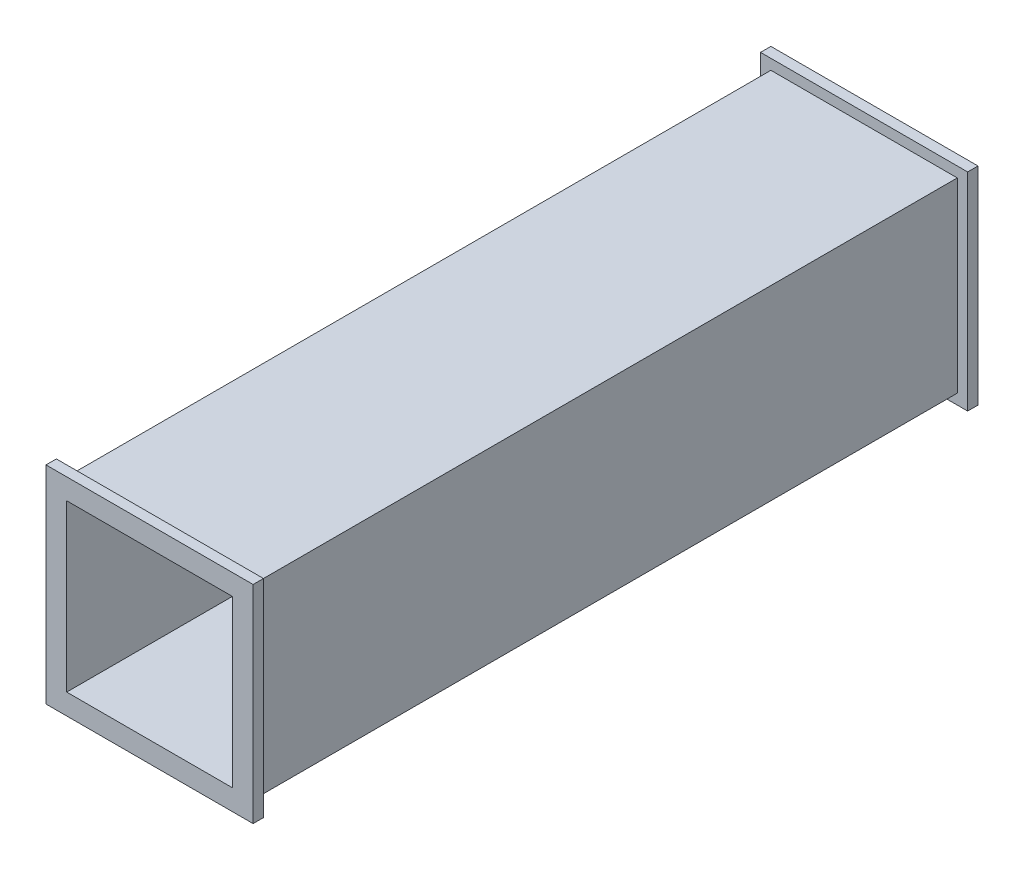
SolidWorks part; units mm, degrees
ref_plane "Front Plane" through (0, 0, 0) normal (0, 0, 1) x (1, 0, 0)
ref_plane "Top Plane" through (0, 0, 0) normal (0, 1, 0) x (1, 0, 0)
ref_plane "Right Plane" through (0, 0, 0) normal (1, 0, 0) x (0, 0, -1)
sketch "Sketch1" plane through (0, 0, 0) normal (0, 0, 1) x (1, 0, 0)
  line L1 (-45, 45) -> (45, 45)
  line L2 (-45, 45) -> (-45, -45)
  line L3 (-45, -45) -> (45, -45)
  line L4 (45, 45) -> (45, -45)
  line L5 (-45, 45) -> (45, -45) construction
  line L6 (-45, -45) -> (45, 45) construction
  point P0 (0, 0)
  dimension "D1" = 90
  dimension "D2" = 90
extrude "Boss-Extrude1" add sketch "Sketch1" along normal blind 350
shell "Shell3" thickness 5
sketch "Sketch2" plane through (-45, 0, 0) normal (-1, 0, 0) x (0, 0, 1)
  line L0 (350, 45) -> (0, 45) construction
  line L1 (125, 25) -> (225, 25)
  line L2 (125, 25) -> (125, -25)
  line L3 (125, -25) -> (225, -25)
  line L4 (225, 25) -> (225, -25)
  line L5 (125, 25) -> (225, -25) construction
  line L6 (125, -25) -> (225, 25) construction
  line L7 (350, 45) -> (350, -45) construction
  point P0 (175, 0)
  point P7 (0, 0)
  point P8 (0, 0)
  point P9 (175, 45)
  point P10 (0, 0)
  point P13 (350, 0)
  dimension "D1" = 100
  dimension "D2" = 50
extrude "Cut-Extrude1" cut sketch "Sketch2" against normal blind 20
ref_plane "Plane1" through (45, 45, 350) normal (0, 1, 0) x (1, 0, 0)
sketch "Sketch9" plane through (0, 0, 350) normal (0, 0, 1) x (1, 0, 0)
  line L0 (50, 50) -> (-50, 50)
  line L1 (-50, 50) -> (-50, -50)
  line L2 (-50, -50) -> (50, -50)
  line L3 (50, -50) -> (50, 50)
  line L4 (45, -45) -> (45, 45)
  line L5 (45, 45) -> (-45, 45)
  line L6 (-45, 45) -> (-45, -45)
  line L7 (-45, -45) -> (45, -45)
  line L8 (45, -45) -> (45, 45)
  line L9 (45, 45) -> (-45, 45)
  line L10 (-45, 45) -> (-45, -45)
  line L11 (-45, -45) -> (45, -45)
  dimension "D1" = 0
  dimension "D2" = 5
extrude "Boss-Extrude8" add sketch "Sketch9" against normal blind 5
sketch "Sketch10" plane through (0, 0, 0) normal (0, 0, -1) x (-1, 0, 0)
  line L0 (50, 50) -> (-50, 50)
  line L1 (-50, 50) -> (-50, -50)
  line L2 (-50, -50) -> (50, -50)
  line L3 (50, -50) -> (50, 50)
  line L4 (-45, 45) -> (-45, -45)
  line L5 (-45, -45) -> (45, -45)
  line L6 (45, -45) -> (45, 45)
  line L7 (45, 45) -> (-45, 45)
  line L8 (-45, 45) -> (-45, -45)
  line L9 (-45, -45) -> (45, -45)
  line L10 (45, -45) -> (45, 45)
  line L11 (45, 45) -> (-45, 45)
  dimension "D1" = 0
  dimension "D2" = 5
extrude "Boss-Extrude9" add sketch "Sketch10" against normal blind 5
